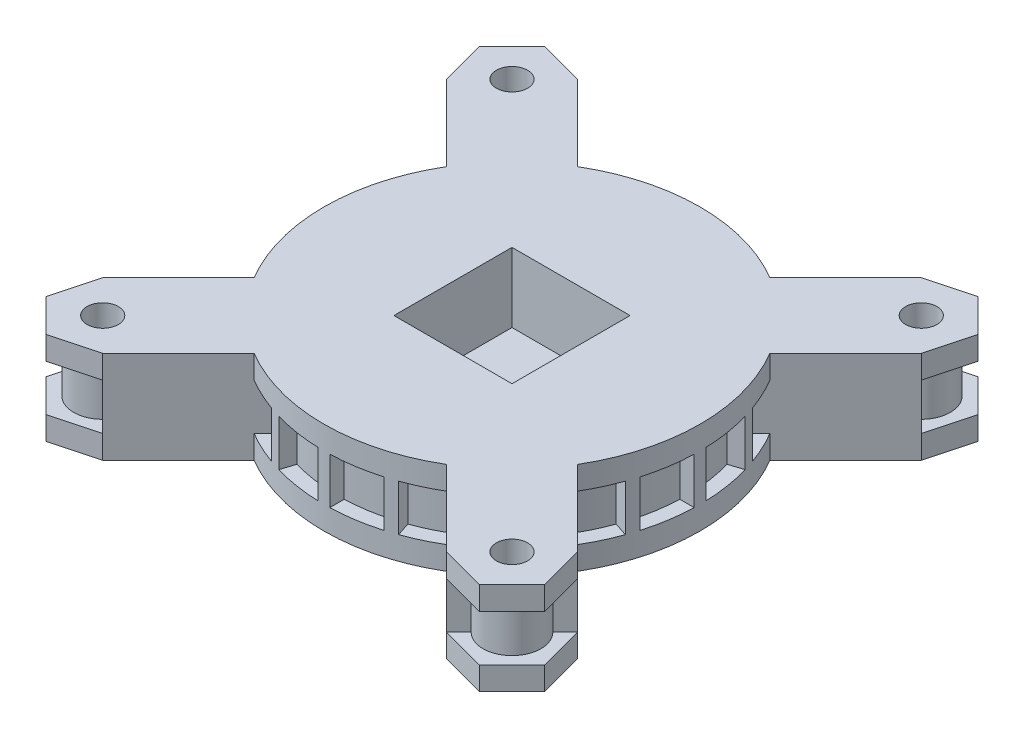
SolidWorks part; units mm, degrees
ref_plane "Front Plane" through (0, 0, 0) normal (0, 0, 1) x (1, 0, 0)
ref_plane "Top Plane" through (0, 0, 0) normal (0, 1, 0) x (1, 0, 0)
ref_plane "Right Plane" through (0, 0, 0) normal (1, 0, 0) x (0, 0, -1)
ref_plane "Plane3" through (0, 4, 0) normal (0, 1, 0) x (1, 0, 0)
ref_plane "Plane4" through (0, 12, 0) normal (0, 1, 0) x (1, 0, 0)
ref_plane "Plane5" through (0, 16, 0) normal (0, 1, 0) x (1, 0, 0)
sketch "Sketch11" plane through (0, 0, 0) normal (0, 1, 0) x (1, 0, 0)
  line L0 (27.9307, -16.617) -> (41.0122, -29.6985)
  line L1 (27.9307, 16.617) -> (41.0122, 29.6985)
  line L2 (16.617, 27.9307) -> (29.6985, 41.0122)
  line L3 (16.617, -27.9307) -> (29.6985, -41.0122)
  line L4 (-16.617, -27.9307) -> (-29.6985, -41.0122)
  line L5 (-27.9307, -16.617) -> (-41.0122, -29.6985)
  line L6 (-27.9307, 16.617) -> (-41.0122, 29.6985)
  line L7 (-16.617, 27.9307) -> (-29.6985, 41.0122)
  line L8 (43.0827, -37.4259) -> (41.0122, -29.6985)
  line L9 (37.4259, -43.0827) -> (43.0827, -37.4259)
  line L13 (41.0122, 29.6985) -> (43.0827, 37.4259)
  line L14 (43.0827, 37.4259) -> (37.4259, 43.0827)
  line L15 (37.4259, 43.0827) -> (29.6985, 41.0122)
  line L16 (30.4564, 30.4564) -> (33.2848, 27.6279) [skipped]
  line L17 (28.6632, 37.1485) -> (27.6279, 33.2848) [skipped]
  line L18 (37.1485, 28.6632) -> (41.0122, 29.6985) [skipped]
  line L19 (29.6985, -41.0122) -> (37.4259, -43.0827)
  line L20 (-37.4259, -43.0827) -> (-29.6985, -41.0122)
  line L21 (-43.0827, -37.4259) -> (-37.4259, -43.0827)
  line L22 (-41.0122, -29.6985) -> (-43.0827, -37.4259)
  line L23 (-43.0827, 37.4259) -> (-41.0122, 29.6985)
  line L24 (-37.4259, 43.0827) -> (-43.0827, 37.4259)
  line L25 (-29.6985, 41.0122) -> (-37.4259, 43.0827)
  arc A0 (16.617, 27.9307) -> (-16.617, 27.9307) centre (0, 0) ccw
  arc A1 (-27.9307, 16.617) -> (-27.9307, -16.617) centre (0, 0) ccw
  arc A2 (-16.617, -27.9307) -> (16.617, -27.9307) centre (0, 0) ccw
  arc A3 (27.9307, -16.617) -> (27.9307, 16.617) centre (0, 0) ccw
  point P23 (0, 0)
  point P46 (0, 0)
extrude "Boss-Extrude8" add sketch "Sketch11" along normal blind 4
sketch "Sketch12" plane through (0, 4, 0) normal (0, 1, 0) x (1, 0, 0)
  line L0 (38.8909, 31.8198) -> (41.0122, 29.6985)
  line L2 (26.1019, 14.7882) -> (41.0122, 29.6985)
  line L3 (14.7882, 26.1019) -> (29.6985, 41.0122)
  line L4 (29.6985, 41.0122) -> (31.8198, 38.8909)
  line L5 (26.1019, -14.7882) -> (41.0122, -29.6985)
  line L6 (41.0122, -29.6985) -> (38.8909, -31.8198)
  line L7 (31.8198, -38.8909) -> (29.6985, -41.0122)
  line L8 (14.7882, -26.1019) -> (29.6985, -41.0122)
  line L9 (-14.7882, -26.1019) -> (-29.6985, -41.0122)
  line L10 (-29.6985, -41.0122) -> (-31.8198, -38.8909)
  line L11 (-38.8909, -31.8198) -> (-41.0122, -29.6985)
  line L12 (-26.1019, -14.7882) -> (-41.0122, -29.6985)
  line L13 (-26.1019, 14.7882) -> (-41.0122, 29.6985)
  line L14 (-41.0122, 29.6985) -> (-38.8909, 31.8198)
  line L15 (-31.8198, 38.8909) -> (-29.6985, 41.0122)
  line L16 (-14.7882, 26.1019) -> (-29.6985, 41.0122)
  line L17 (-1, 32.4846) -> (-1, 29.9833)
  line L18 (10.9894, 30.5857) -> (10.2164, 28.2068)
  line L19 (1, 32.4846) -> (1, 29.9833)
  line L20 (9.0872, 31.2037) -> (8.3143, 28.8249)
  line L25 (31.2037, 9.0872) -> (28.8249, 8.3143)
  line L26 (30.5857, 10.9894) -> (28.2068, 10.2164)
  line L27 (32.4846, -1) -> (29.9833, -1)
  line L28 (32.4846, 1) -> (29.9833, 1)
  line L29 (30.5857, -10.9894) -> (28.2068, -10.2164)
  line L30 (31.2037, -9.0872) -> (28.8249, -8.3143)
  line L35 (9.0872, -31.2037) -> (8.3143, -28.8249)
  line L36 (10.9894, -30.5857) -> (10.2164, -28.2068)
  line L37 (-1, -32.4846) -> (-1, -29.9833)
  line L38 (1, -32.4846) -> (1, -29.9833)
  line L39 (-10.9894, -30.5857) -> (-10.2164, -28.2068)
  line L40 (-9.0872, -31.2037) -> (-8.3143, -28.8249)
  line L45 (-31.2037, -9.0872) -> (-28.8249, -8.3143)
  line L46 (-30.5857, -10.9894) -> (-28.2068, -10.2164)
  line L47 (-32.4846, 1) -> (-29.9833, 1)
  line L48 (-32.4846, -1) -> (-29.9833, -1)
  line L49 (-30.5857, 10.9894) -> (-28.2068, 10.2164)
  line L50 (-31.2037, 9.0872) -> (-28.8249, 8.3143)
  line L55 (-9.0872, 31.2037) -> (-8.3143, 28.8249)
  line L56 (-10.9894, 30.5857) -> (-10.2164, 28.2068)
  line L57 (-19.4257, 28.4385) -> (-12.3592, 18.7123) [skipped]
  line L58 (-21.0438, 27.263) -> (-13.9773, 17.5367) [skipped]
  line L59 (-27.263, 21.0438) -> (-17.5367, 13.9773) [skipped]
  line L60 (-28.4385, 19.4257) -> (-18.7123, 12.3592) [skipped]
  line L61 (19.4257, 28.4385) -> (12.3592, 18.7123) [skipped]
  line L62 (21.0438, 27.263) -> (13.9773, 17.5367) [skipped]
  line L63 (27.263, 21.0438) -> (17.5367, 13.9773) [skipped]
  line L64 (28.4385, 19.4257) -> (18.7123, 12.3592) [skipped]
  line L65 (27.263, -21.0438) -> (17.5367, -13.9773) [skipped]
  line L66 (28.4385, -19.4257) -> (18.7123, -12.3592) [skipped]
  line L67 (21.0438, -27.263) -> (13.9773, -17.5367) [skipped]
  line L68 (19.4257, -28.4385) -> (12.3592, -18.7123) [skipped]
  line L69 (-19.4257, -28.4385) -> (-12.3592, -18.7123) [skipped]
  line L70 (-21.0438, -27.263) -> (-13.9773, -17.5367) [skipped]
  line L71 (-27.263, -21.0438) -> (-17.5367, -13.9773) [skipped]
  line L72 (-28.4385, -19.4257) -> (-18.7123, -12.3592) [skipped]
  arc A0 (14.7882, 26.1019) -> (10.2164, 28.2068) centre (0, 0) ccw
  arc A1 (38.8909, 31.8198) -> (31.8198, 38.8909) centre (35.3553, 35.3553) ccw
  arc A2 (31.8198, -38.8909) -> (38.8909, -31.8198) centre (35.3553, -35.3553) ccw
  arc A3 (-38.8909, -31.8198) -> (-31.8198, -38.8909) centre (-35.3553, -35.3553) ccw
  arc A4 (-31.8198, 38.8909) -> (-38.8909, 31.8198) centre (-35.3553, 35.3553) ccw
  arc A5 (-26.1019, 14.7882) -> (-28.2068, 10.2164) centre (0, 0) ccw
  arc A6 (-14.7882, -26.1019) -> (-10.2164, -28.2068) centre (0, 0) ccw
  arc A7 (26.1019, -14.7882) -> (28.2068, -10.2164) centre (0, 0) ccw
  arc A8 (-31.2037, -9.0872) -> (-30.5857, -10.9894) centre (0, 0) ccw
  arc A9 (-32.4846, 1) -> (-32.4846, -1) centre (0, 0) ccw
  arc A10 (-30.5857, 10.9894) -> (-31.2037, 9.0872) centre (0, 0) ccw
  arc A11 (-10.9894, -30.5857) -> (-9.0872, -31.2037) centre (0, 0) ccw
  arc A12 (-28.8249, 8.3143) -> (-29.9833, 1) centre (0, 0) ccw
  arc A13 (-29.9833, -1) -> (-28.8249, -8.3143) centre (0, 0) ccw
  arc A14 (-28.2068, -10.2164) -> (-26.1019, -14.7882) centre (0, 0) ccw
  arc A15 (-9.0872, 31.2037) -> (-10.9894, 30.5857) centre (0, 0) ccw
  arc A16 (1, 32.4846) -> (-1, 32.4846) centre (0, 0) ccw
  arc A17 (10.9894, 30.5857) -> (9.0872, 31.2037) centre (0, 0) ccw
  arc A18 (31.2037, 9.0872) -> (30.5857, 10.9894) centre (0, 0) ccw
  arc A19 (32.4846, -1) -> (32.4846, 1) centre (0, 0) ccw
  arc A20 (30.5857, -10.9894) -> (31.2037, -9.0872) centre (0, 0) ccw
  arc A21 (-1, -32.4846) -> (1, -32.4846) centre (0, 0) ccw
  arc A22 (9.0872, -31.2037) -> (10.9894, -30.5857) centre (0, 0) ccw
  arc A23 (10.2164, -28.2068) -> (14.7882, -26.1019) centre (0, 0) ccw
  arc A24 (-8.3143, -28.8249) -> (-1, -29.9833) centre (0, 0) ccw
  arc A25 (28.8249, -8.3143) -> (29.9833, -1) centre (0, 0) ccw
  arc A26 (29.9833, 1) -> (28.8249, 8.3143) centre (0, 0) ccw
  arc A27 (28.2068, 10.2164) -> (26.1019, 14.7882) centre (0, 0) ccw
  arc A28 (-10.2164, 28.2068) -> (-14.7882, 26.1019) centre (0, 0) ccw
  arc A29 (-1, 29.9833) -> (-8.3143, 28.8249) centre (0, 0) ccw
  arc A30 (8.3143, 28.8249) -> (1, 29.9833) centre (0, 0) ccw
  arc A31 (1, -29.9833) -> (8.3143, -28.8249) centre (0, 0) ccw
  point P35 (0, 0)
  point P115 (0, 0)
  dimension "D1" = 20
  dimension "D2" = 4
extrude "Boss-Extrude10" add sketch "Sketch12" along normal blind 8
sketch "Sketch13" plane through (0, 12, 0) normal (0, 1, 0) x (1, 0, 0)
  line L0 (27.9307, -16.617) -> (41.0122, -29.6985)
  line L1 (43.0827, -37.4259) -> (41.0122, -29.6985)
  line L2 (27.9307, 16.617) -> (41.0122, 29.6985)
  line L3 (16.617, 27.9307) -> (29.6985, 41.0122)
  line L4 (37.4259, -43.0827) -> (43.0827, -37.4259)
  line L5 (41.0122, 29.6985) -> (43.0827, 37.4259)
  line L6 (43.0827, 37.4259) -> (37.4259, 43.0827)
  line L7 (37.4259, 43.0827) -> (29.6985, 41.0122)
  line L11 (27.6279, 33.2848) -> (30.4564, 30.4564) [skipped]
  line L12 (37.1485, 28.6632) -> (41.0122, 29.6985) [skipped]
  line L13 (29.6985, 41.0122) -> (28.6632, 37.1485) [skipped]
  line L14 (29.6985, -41.0122) -> (37.4259, -43.0827)
  line L15 (16.617, -27.9307) -> (29.6985, -41.0122)
  line L16 (-16.617, -27.9307) -> (-29.6985, -41.0122)
  line L17 (-37.4259, -43.0827) -> (-29.6985, -41.0122)
  line L18 (-43.0827, -37.4259) -> (-37.4259, -43.0827)
  line L19 (-41.0122, -29.6985) -> (-43.0827, -37.4259)
  line L20 (-27.9307, -16.617) -> (-41.0122, -29.6985)
  line L21 (-27.9307, 16.617) -> (-41.0122, 29.6985)
  line L22 (-43.0827, 37.4259) -> (-41.0122, 29.6985)
  line L23 (-37.4259, 43.0827) -> (-43.0827, 37.4259)
  line L24 (-29.6985, 41.0122) -> (-37.4259, 43.0827)
  line L25 (-16.617, 27.9307) -> (-29.6985, 41.0122)
  arc A0 (16.617, 27.9307) -> (-16.617, 27.9307) centre (0, 0) ccw
  arc A1 (-27.9307, 16.617) -> (-27.9307, -16.617) centre (0, 0) ccw
  arc A2 (-16.617, -27.9307) -> (16.617, -27.9307) centre (0, 0) ccw
  arc A3 (27.9307, -16.617) -> (27.9307, 16.617) centre (0, 0) ccw
  point P37 (0, 0)
extrude "Boss-Extrude11" add sketch "Sketch13" along normal blind 4
sketch "Sketch14" plane through (0, 16, 0) normal (0, 1, 0) x (1, 0, 0)
  line L1 (-10.2, -10.2) -> (10.2, -10.2)
  line L2 (-10.2, -10.2) -> (-10.2, 10.2)
  line L3 (-10.2, 10.2) -> (10.2, 10.2)
  line L4 (10.2, -10.2) -> (10.2, 10.2)
  line L5 (-10.2, -10.2) -> (10.2, 10.2) construction
  line L6 (-10.2, 10.2) -> (10.2, -10.2) construction
  circle A1 centre (-35.3553, 35.3553) radius 2.7
  circle A2 centre (35.3553, 35.3553) radius 2.7
  circle A3 centre (35.3553, -35.3553) radius 2.7
  circle A4 centre (-35.3553, -35.3553) radius 2.7
  point P1 (0, 0)
  point P17 (0, 0)
extrude "Cut-Extrude1" cut sketch "Sketch14" against normal blind 12
